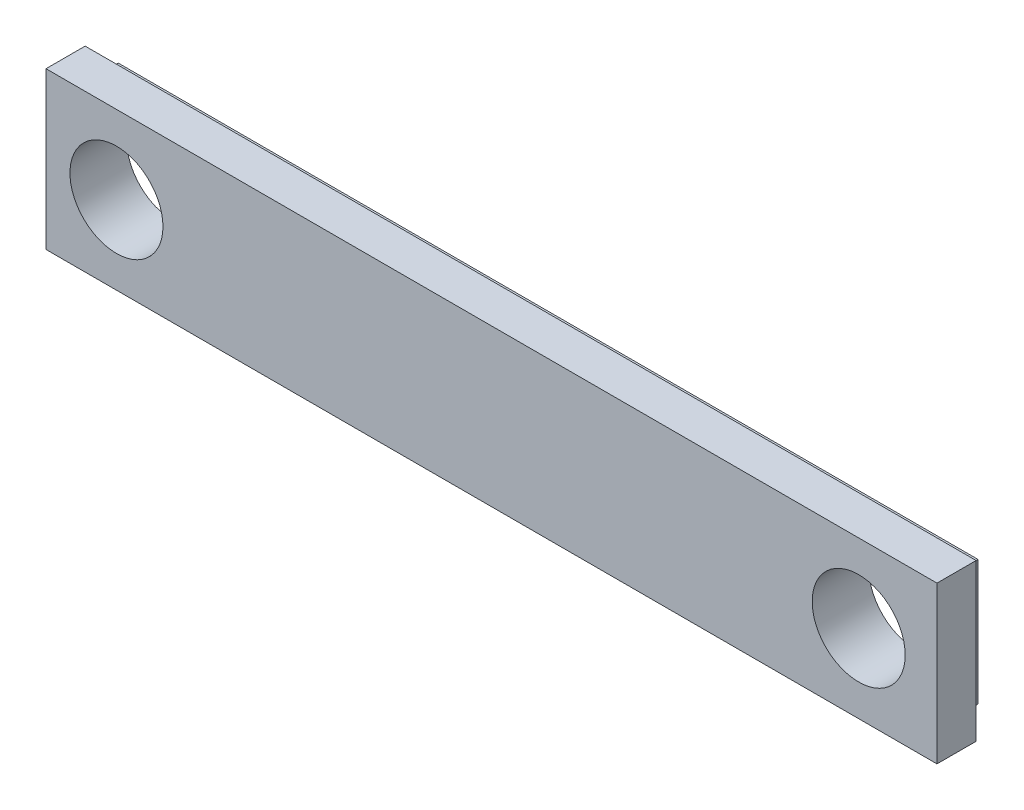
SolidWorks part; units mm, degrees
ref_plane "Front Plane" through (0, 0, 0) normal (0, 0, 1) x (1, 0, 0)
ref_plane "Top Plane" through (0, 0, 0) normal (0, 1, 0) x (1, 0, 0)
ref_plane "Right Plane" through (0, 0, 0) normal (1, 0, 0) x (0, 0, -1)
sketch "Sketch1" plane through (0, 0, 0) normal (0, 0, 1) x (1, 0, 0)
  line L0 (-161.9, 2) -> (-216.8, 2)
  line L1 (-161.4, 10.5) -> (-217.3, 10.5) construction
  line L2 (-161.4, 10.5) -> (-161.4, 1.5) construction
  line L3 (-161.4, 1.5) -> (-217.3, 1.5) construction
  line L4 (-217.3, 10.5) -> (-217.3, 1.5) construction
  line L5 (-216.8, 10) -> (-216.8, 2)
  line L6 (-161.9, 10) -> (-216.8, 10)
  line L7 (-161.9, 10) -> (-161.9, 2)
  circle A0 centre (-165.9, 6) radius 2.97
  circle A1 centre (-213.3, 6) radius 2.97
  dimension "D2" = 5.94
  dimension "D1" = 0.5
extrude "Boss-Extrude1" add sketch "Sketch1" along normal blind 1.12
sketch "Sketch2" plane through (0, 0, 1.12) normal (0, 0, 1) x (1, 0, 0)
  line L0 (-216.8, 2) -> (-161.9, 2) construction
  line L1 (-161.9, 10) -> (-216.8, 10) construction
  line L2 (-161.9, 10) -> (-161.9, 2) construction
  line L3 (-161.9, 2) -> (-216.8, 2) construction
  line L4 (-216.8, 10) -> (-216.8, 2) construction
  line L5 (-161.9, 2) -> (-161.9, 10) construction
  line L6 (-161.9, 10) -> (-216.8, 10) construction
  line L7 (-160.9, 11) -> (-217.8, 11)
  line L8 (-217.8, 11) -> (-217.8, 1)
  line L9 (-160.9, 1) -> (-217.8, 1)
  line L10 (-160.9, 11) -> (-160.9, 1)
  circle A0 centre (-213.3, 6) radius 2.97
  circle A1 centre (-165.9, 6) radius 2.97
  circle A2 centre (-213.3, 6) radius 2.97 construction
  point P6 (-189.35, 2)
  point P7 (-189.35, 2)
  point P8 (-161.9, 6)
  point P11 (-161.9, 6)
  dimension "D1" = 1
extrude "Boss-Extrude3" add sketch "Sketch2" along normal blind 2.5 contours A0 | L3 L4 L1 L2 | A1 | L7 L8 L9 L10
